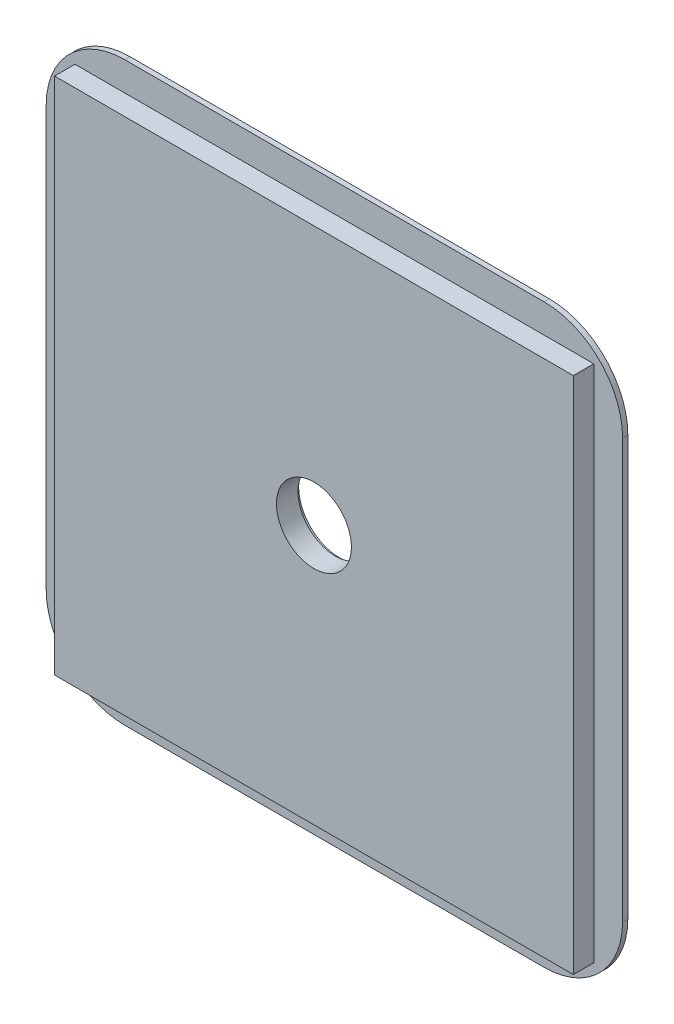
SolidWorks part; units mm, degrees
ref_plane "前视基准面" through (0, 0, 0) normal (0, 0, 1) x (1, 0, 0)
ref_plane "上视基准面" through (0, 0, 0) normal (0, 1, 0) x (1, 0, 0)
ref_plane "右视基准面" through (0, 0, 0) normal (1, 0, 0) x (0, 0, -1)
other "Configuration Table"
sketch "草图1" plane through (0, 0, 0) normal (0, 0, 1) x (1, 0, 0)
  line L1 (-49.5, 49.5) -> (49.5, 49.5)
  line L2 (-49.5, 49.5) -> (-49.5, -49.5)
  line L3 (-49.5, -49.5) -> (49.5, -49.5)
  line L4 (49.5, 49.5) -> (49.5, -49.5)
  line L5 (-49.5, 49.5) -> (49.5, -49.5) construction
  line L6 (-49.5, -49.5) -> (49.5, 49.5) construction
  point P0 (0, 0)
  dimension "D1" = 99
extrude "凸台-拉伸1" add sketch "草图1" along normal blind 3.9
sketch "草图2" plane through (0, 0, 0) normal (0, 0, -1) x (-1, 0, 0)
  line L1 (-55, 55) -> (55, 55)
  line L2 (-55, 55) -> (-55, -55)
  line L3 (-55, -55) -> (55, -55)
  line L4 (55, 55) -> (55, -55)
  line L5 (-55, 55) -> (55, -55) construction
  line L6 (-55, -55) -> (55, 55) construction
  point P0 (0, 0)
  dimension "D1" = 110
extrude "凸台-拉伸2" add sketch "草图2" along normal blind 1
sketch "草图3" plane through (0, 0, -1) normal (0, 0, -1) x (-1, 0, 0)
  circle A0 centre (0, 0) radius 7.15
  dimension "D1" = 14.3
extrude "切除-拉伸1" cut sketch "草图3" against normal through all
sketch "草图5" plane through (0, 0, -1) normal (0, 0, -1) x (-1, 0, 0)
  circle A0 centre (0, 0) radius 7.825
  dimension "D1" = 15.65
extrude "切除-拉伸2" cut sketch "草图5" against normal blind 0.8
fillet "圆角1" radius 15 4 edges at (-55, -55, -0.5) (-55, 55, -0.5) (55, 55, -0.5) (55, -55, -0.5)
